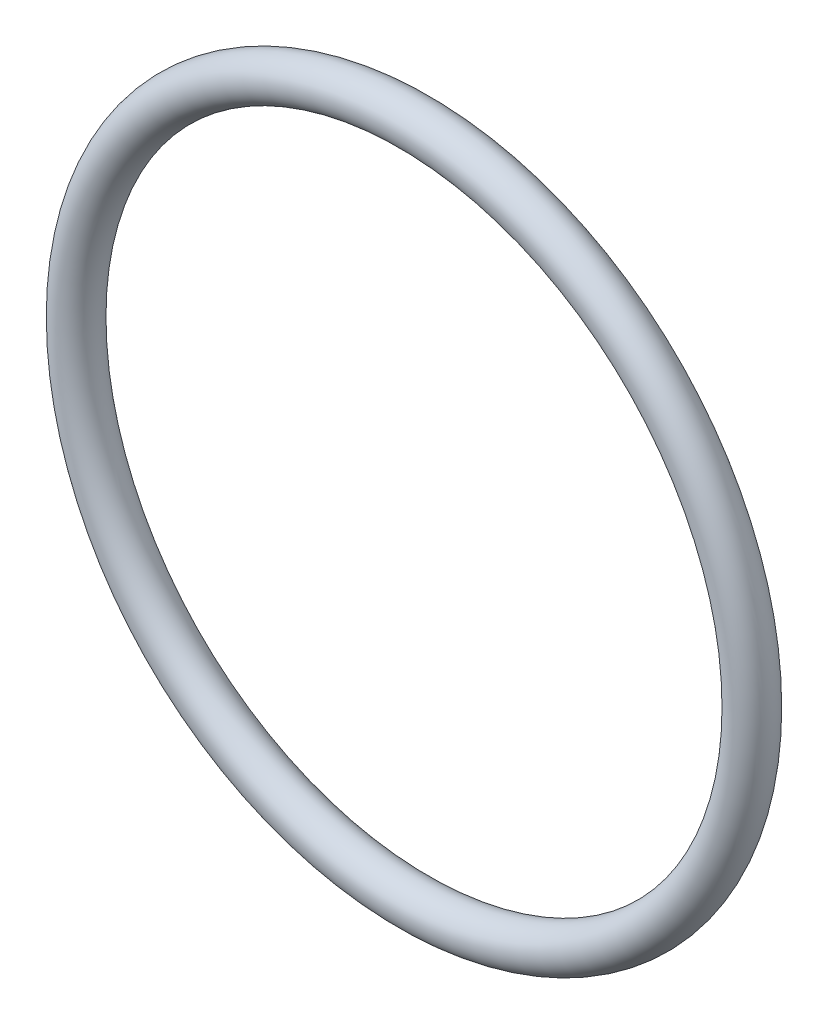
SolidWorks part; units mm, degrees
material "Caucho natural"
ref_plane "Alzado" through (0, 0, 0) normal (0, 0, 1) x (1, 0, 0)
ref_plane "Planta" through (0, 0, 0) normal (0, 1, 0) x (1, 0, 0)
ref_plane "Vista lateral" through (0, 0, 0) normal (1, 0, 0) x (0, 0, -1)
sketch "Croquis1" plane through (0, 0, 0) normal (0, 0, 1) x (1, 0, 0)
  circle A1 centre (0, 0) radius 40
  dimension "D2" = 80
sweep "Barrer1" add path "Croquis1" circular profile diameter 5 parameters "D3"=5
ref_plane "Plano1" through (0, 0, 0) normal (1, 0, 0) x (0, 0, -1)
ref_plane "Plano2" through (0, 0, 0) normal (0, 1, 0) x (1, 0, 0)
